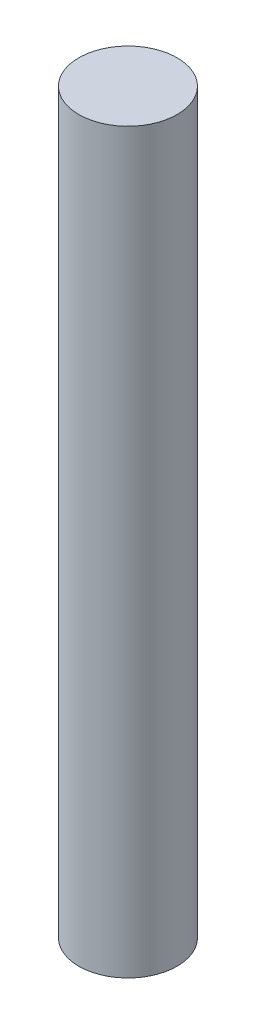
SolidWorks part; units mm, degrees
ref_plane "前视基准面" through (0, 0, 0) normal (0, 0, 1) x (1, 0, 0)
ref_plane "上视基准面" through (0, 0, 0) normal (0, 1, 0) x (1, 0, 0)
ref_plane "右视基准面" through (0, 0, 0) normal (1, 0, 0) x (0, 0, -1)
other "Configuration Table"
sketch "草图1" plane through (0, 0, 0) normal (0, 1, 0) x (1, 0, 0)
  circle A0 centre (0, 0) radius 0.6
  dimension "D1" = 1.2
extrude "凸台-拉伸1" add sketch "草图1" along normal blind 9
